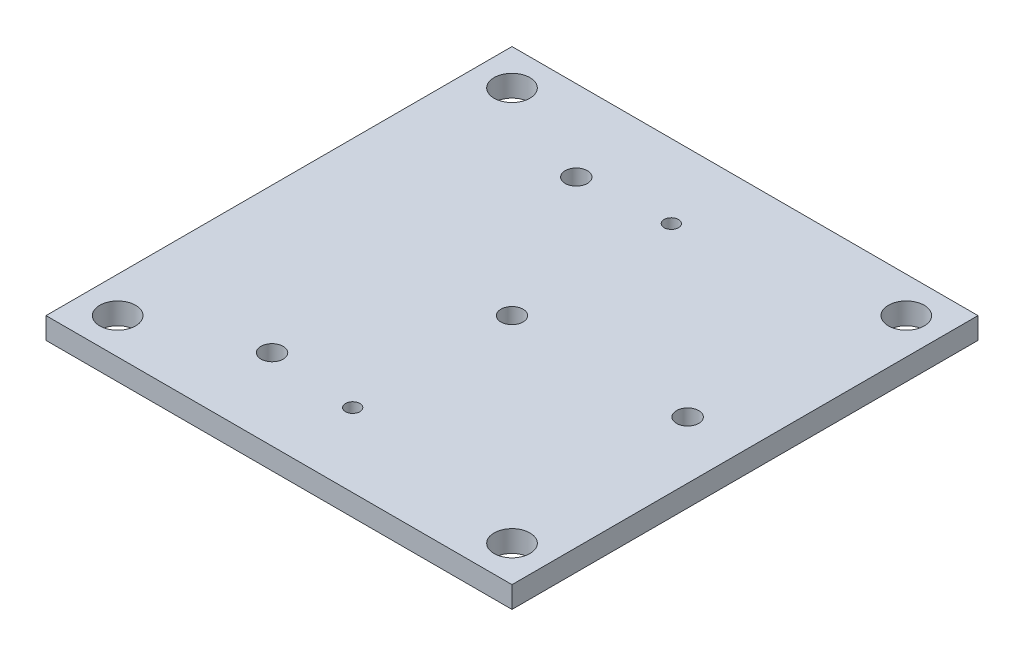
SolidWorks part; units mm, degrees
ref_plane "前视基准面" through (0, 0, 0) normal (0, 0, 1) x (1, 0, 0)
ref_plane "上视基准面" through (0, 0, 0) normal (0, 1, 0) x (1, 0, 0)
ref_plane "右视基准面" through (0, 0, 0) normal (1, 0, 0) x (0, 0, -1)
sketch "草图8" plane through (0, 1803, 0) normal (0, -1, 0) x (1, 0, 0)
  circle A0 centre (2814.7798, -929.5) radius 58
  circle A4 centre (2814.7798, -929.5) radius 3
  point P12 (2814.7798, -929.5)
extrude "凸台-拉伸5" add sketch "草图8" along normal blind 6 separate body
sketch "草图9" plane through (0, 1797, 0) normal (0, -1, 0) x (1, 0, 0)
  circle A0 centre (2814.7798, -885.05) radius 2
  circle A1 centre (2814.7798, -973.95) radius 2
extrude "凸台-拉伸6" add sketch "草图9" against normal blind 12
sketch "草图10" plane through (0, 1797, 0) normal (0, -1, 0) x (1, 0, 0)
  line L1 (2749.7798, -864.5) -> (2749.7798, -994.5)
  line L2 (2749.7798, -994.5) -> (2879.7798, -994.5)
  line L3 (2879.7798, -994.5) -> (2879.7798, -864.5)
  line L4 (2879.7798, -864.5) -> (2749.7798, -864.5)
  line L6 (2879.7798, -864.5) -> (2879.7798, -874.5)
  circle A0 centre (2814.7798, -929.5) radius 65 construction
  circle A1 centre (2869.7798, -874.5) radius 5
  circle A2 centre (2759.7798, -874.5) radius 5
  circle A3 centre (2759.7798, -984.5) radius 5
  circle A4 centre (2869.7798, -984.5) radius 5
  circle A5 centre (2814.7798, -929.5) radius 58
  circle M5 centre (2814.7798, -929.5) radius 58
  dimension "D1" = 2
  dimension "D2" = 2
extrude "凸台-拉伸8" add sketch "草图10" against normal blind 6 contours L3 L4 L1 L2 A4 A3 A2 A1 M5
sketch "草图12" plane through (0, 1809, 0) normal (0, 1, 0) x (1, 0, 0)
  circle A0 centre (2814.7798, 973.95) radius 2
  circle A1 centre (2814.7798, 973.95) radius 2 construction
  dimension "D1" = 0
extrude "切除-拉伸1" cut sketch "草图12" against normal blind 30
sketch "草图13" plane through (0, 1809, 0) normal (0, 1, 0) x (1, 0, 0)
  circle A0 centre (2814.7798, 885.05) radius 2
  circle A1 centre (2814.7798, 885.05) radius 2 construction
  dimension "D1" = 0
extrude "切除-拉伸2" cut sketch "草图13" against normal blind 30
sketch "草图14" plane through (0, 1803, 0) normal (0, 1, 0) x (1, 0, 0)
  circle A0 centre (2814.7798, 929.5) radius 3.1
  circle A1 centre (2814.7798, 929.5) radius 3 construction
  dimension "D1" = 0
extrude "切除-拉伸3" cut sketch "草图14" against normal blind 6
sketch "草图15" plane through (0, 1803, 0) normal (0, 1, 0) x (1, 0, 0)
  circle A0 centre (2863.7798, 929.5) radius 3.1
  circle A1 centre (2814.7798, 929.5) radius 3.1 construction
  circle A2 centre (2790.2798, 887.0648) radius 3.1
  circle A3 centre (2790.2798, 971.9352) radius 3.1
  point P11 (2814.7798, 929.5)
  dimension "D1" = 49
  dimension "D2" = 3
extrude "切除-拉伸4" cut sketch "草图15" against normal blind 6
